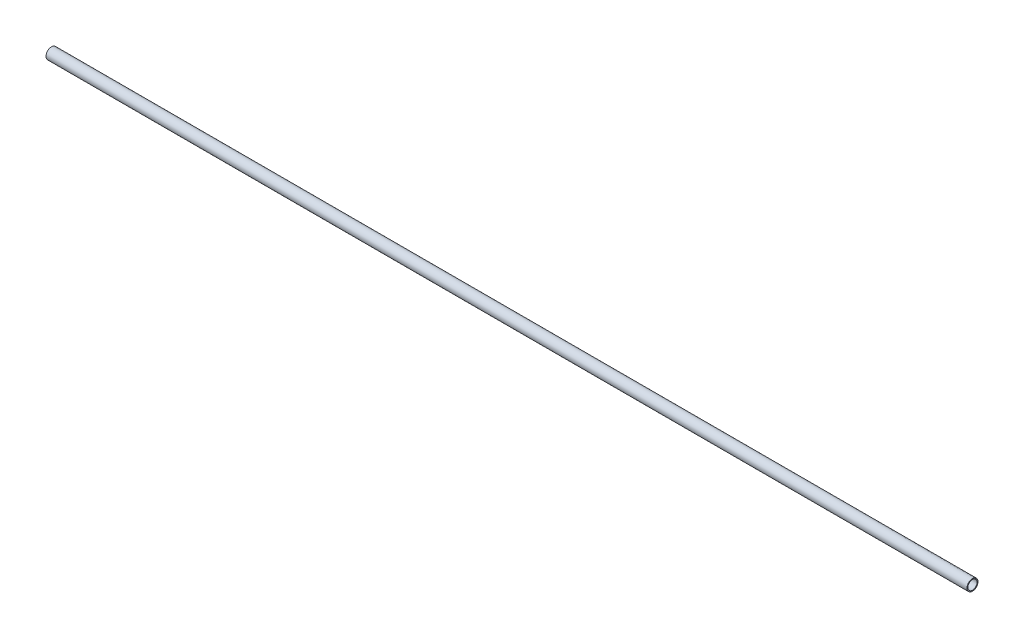
SolidWorks part; units mm, degrees
material "windcatcher"
ref_plane "Front Plane" through (0, 0, 0) normal (0, 0, 1) x (1, 0, 0)
ref_plane "Top Plane" through (0, 0, 0) normal (0, 1, 0) x (1, 0, 0)
ref_plane "Right Plane" through (0, 0, 0) normal (1, 0, 0) x (0, 0, -1)
sketch "Sketch1" plane through (0, 0, 0) normal (1, 0, 0) x (0, 0, -1)
  circle A0 centre (0, 0) radius 6
  circle A1 centre (0, 0) radius 5
  dimension "D1" = 12
  dimension "D2" = 10
extrude "Boss-Extrude1" add sketch "Sketch1" along normal mid plane 1000
